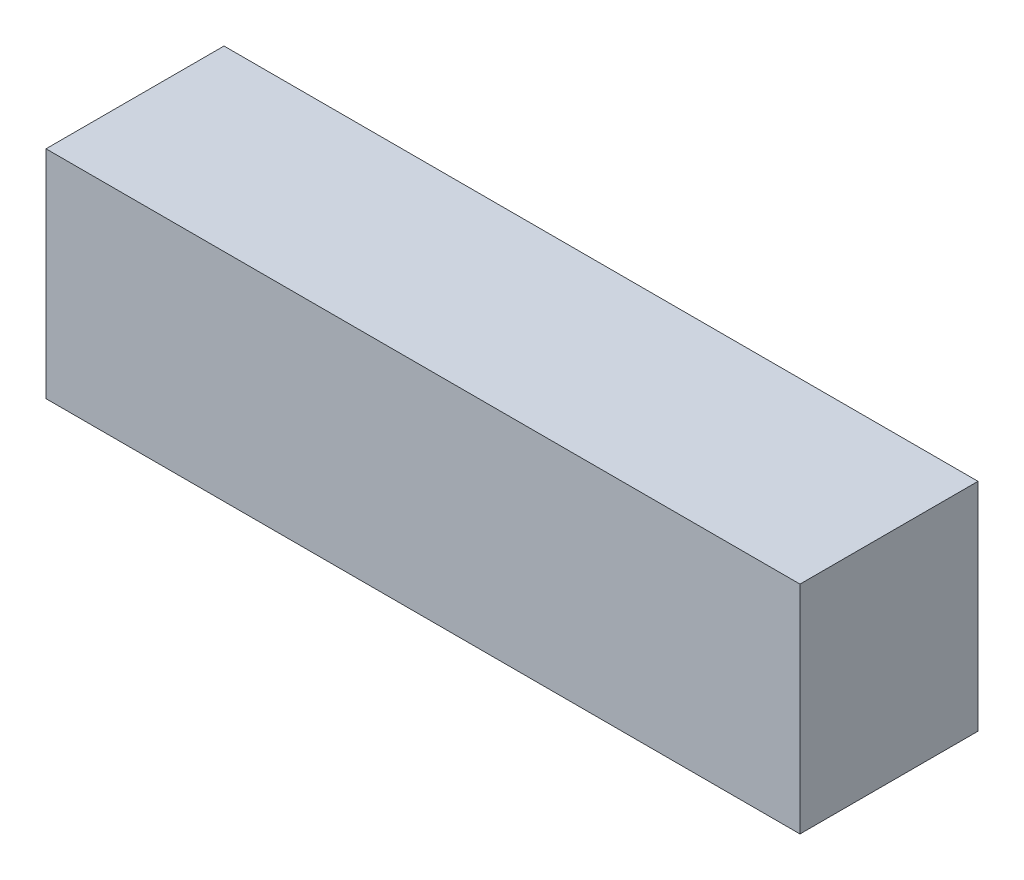
SolidWorks part; units mm, degrees
material "ABS"
ref_plane "Front Plane" through (0, 0, 0) normal (0, 0, 1) x (1, 0, 0)
ref_plane "Top Plane" through (0, 0, 0) normal (0, 1, 0) x (1, 0, 0)
ref_plane "Right Plane" through (0, 0, 0) normal (1, 0, 0) x (0, 0, -1)
sketch "Sketch1" plane through (0, 0, 0) normal (0, 1, 0) x (1, 0, 0)
  line L1 (0, 0) -> (108, 0)
  line L2 (0, 0) -> (0, 25.5)
  line L3 (0, 25.5) -> (108, 25.5)
  line L4 (108, 0) -> (108, 25.5)
  dimension "D1" = 25.5
  dimension "D2" = 108
extrude "Boss-Extrude1" add sketch "Sketch1" along normal blind 31
